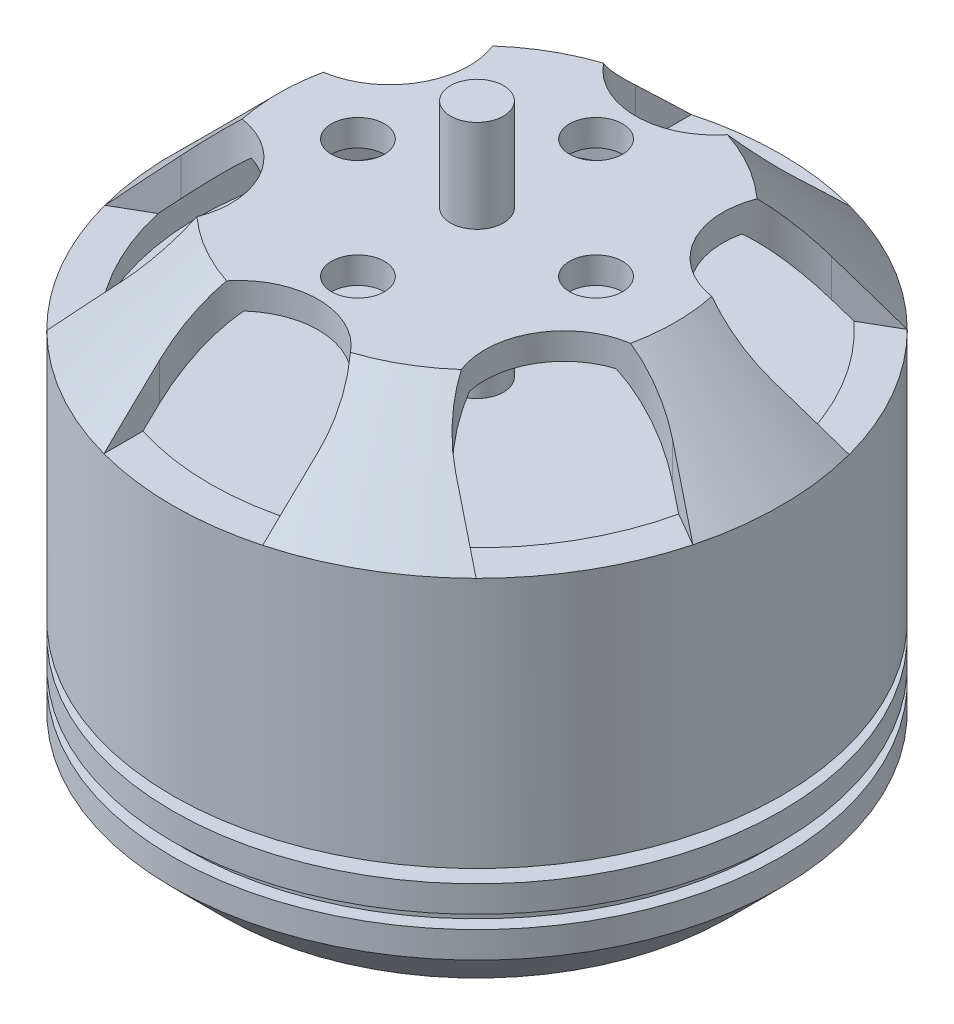
SolidWorks part; units mm, degrees
ref_plane "前视基准面" through (0, 0, 0) normal (0, 0, 1) x (1, 0, 0)
ref_plane "上视基准面" through (0, 0, 0) normal (0, 1, 0) x (1, 0, 0)
ref_plane "右视基准面" through (0, 0, 0) normal (1, 0, 0) x (0, 0, -1)
sketch "草图1" plane through (0, 0, 0) normal (0, 0, 1) x (1, 0, 0)
  line L0 (0, 19.2907) -> (0, 0)
  line L1 (1, -2.7093) -> (9.5, -2.7093)
  line L2 (9.5, -2.7093) -> (11.5, -0.7093)
  line L3 (11.5, -0.7093) -> (11.5, 0.2907)
  line L4 (11.5, 11.7907) -> (7.5, 15.7907)
  line L5 (7.5, 15.7907) -> (1, 15.7907)
  line L6 (1, 15.7907) -> (1, 19.2907)
  line L7 (1, 19.2907) -> (0, 19.2907)
  line L8 (0, 0) -> (0, -4.5093)
  line L9 (0, -4.5093) -> (1, -4.5093)
  line L10 (1, -4.5093) -> (1, -2.7093)
  line L11 (2, 14.7907) -> (7.0858, 14.7907)
  line L12 (7.0858, 14.7907) -> (10.5, 11.3764)
  line L13 (10.5, 11.3764) -> (10.5, 10.2516)
  line L14 (10.5, 10.2516) -> (1, 10.2516)
  line L16 (1, 10.2516) -> (1, 13.7907)
  line L17 (1, 13.7907) -> (2, 13.7907)
  line L18 (2, 13.7907) -> (2, 14.7907)
  line L19 (11.5, 0.2907) -> (11, 0.2907)
  line L20 (11, 0.2907) -> (11, 0.7907)
  line L21 (11, 0.7907) -> (11.5, 0.7907)
  line L22 (11.5, 1.7907) -> (9.5, 1.7907)
  line L23 (9.5, 1.7907) -> (9.5, 2.2907)
  line L24 (9.5, 2.2907) -> (11.5, 2.2907)
  line L25 (11.5, 2.2907) -> (11.5, 11.7907)
  line L26 (11.5, 0.7907) -> (11.5, 1.7907)
  dimension "D1" = 23.8
  dimension "D2" = 1.8
  dimension "D3" = 45
  dimension "D4" = 2
  dimension "D5" = 11.5
  dimension "D6" = 1
  dimension "D7" = 1
  dimension "D8" = 3.5
  dimension "D9" = 45
  dimension "D10" = 8.5
  dimension "D11" = 1
  dimension "D12" = 1
  dimension "D13" = 1
  dimension "D14" = 1
  dimension "D15" = 1
  dimension "D16" = 1
  dimension "D17" = 4
  dimension "D18" = 0.5
  dimension "D19" = 0.5
  dimension "D20" = 1
  dimension "D21" = 2
  dimension "D22" = 0.5
  dimension "D23" = 1
revolve "旋转1" add sketch "草图1" angle 360 about L0
sketch "草图2" plane through (0, 15.7907, 0) normal (0, 1, 0) x (1, 0, 0)
  line L0 (0, 0) -> (0, 9) construction
  line L1 (-3, 9) -> (-3, 16.5594)
  line L2 (3, 9) -> (3, 16.5594)
  line L3 (3, 16.5594) -> (-3, 16.5594)
  line L4 (15.8408, 5.6816) -> (12.8408, 10.8778)
  line L5 (9.2942, 1.9019) -> (15.8408, 5.6816)
  line L6 (6.2942, 7.0981) -> (12.8408, 10.8778)
  line L7 (12.8408, -10.8778) -> (15.8408, -5.6816)
  line L8 (6.2942, -7.0981) -> (12.8408, -10.8778)
  line L9 (9.2942, -1.9019) -> (15.8408, -5.6816)
  line L10 (-3, -16.5594) -> (3, -16.5594)
  line L11 (-3, -9) -> (-3, -16.5594)
  line L12 (3, -9) -> (3, -16.5594)
  line L13 (-15.8408, -5.6816) -> (-12.8408, -10.8778)
  line L14 (-9.2942, -1.9019) -> (-15.8408, -5.6816)
  line L15 (-6.2942, -7.0981) -> (-12.8408, -10.8778)
  line L16 (-12.8408, 10.8778) -> (-15.8408, 5.6816)
  line L17 (-6.2942, 7.0981) -> (-12.8408, 10.8778)
  line L18 (-9.2942, 1.9019) -> (-15.8408, 5.6816)
  circle A0 centre (0, 0) radius 4.5 construction
  circle A1 centre (0, 0) radius 8.4571 construction
  circle A2 centre (0, -4.5) radius 1
  circle A3 centre (-4.5, 0) radius 1
  circle A4 centre (0, 4.5) radius 1
  circle A5 centre (4.5, 0) radius 1
  arc A6 (-3, 9) -> (3, 9) centre (0, 9) ccw
  arc A7 (6.2942, 7.0981) -> (9.2942, 1.9019) centre (7.7942, 4.5) ccw
  arc A8 (9.2942, -1.9019) -> (6.2942, -7.0981) centre (7.7942, -4.5) ccw
  arc A9 (3, -9) -> (-3, -9) centre (0, -9) ccw
  arc A10 (-6.2942, -7.0981) -> (-9.2942, -1.9019) centre (-7.7942, -4.5) ccw
  arc A11 (-9.2942, 1.9019) -> (-6.2942, 7.0981) centre (-7.7942, 4.5) ccw
  point P7 (0, 0)
  point P16 (0, 0)
  point P46 (0, 0)
  dimension "D1" = 9
  dimension "D3" = 2
  dimension "D5" = 6
  dimension "D2" = 9
  dimension "D4" = 4
  dimension "D6" = 6
extrude "切除-拉伸1" cut sketch "草图2" against normal blind 4
sketch "草图3" plane through (0, -2.7093, 0) normal (0, -1, 0) x (1, 0, 0)
  circle A0 centre (0, 0) radius 6 construction
  circle A1 centre (0, 0) radius 8 construction
  circle A2 centre (0, 6) radius 1
  circle A3 centre (0, -6) radius 1
  circle A4 centre (-8, 0) radius 1
  circle A5 centre (8, 0) radius 1
  dimension "D1" = 12
  dimension "D2" = 16
  dimension "D3" = 2
extrude "切除-拉伸2" cut sketch "草图3" against normal blind 3
